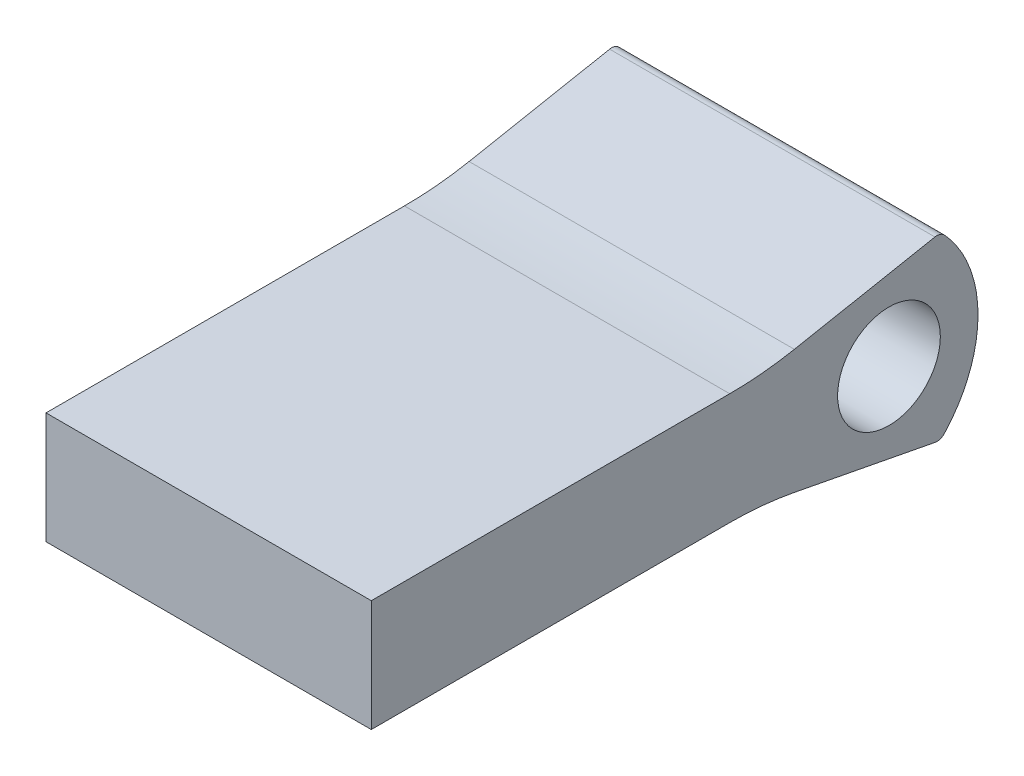
SolidWorks part; units mm, degrees
ref_plane "Front Plane" through (0, 0, 0) normal (0, 0, 1) x (1, 0, 0)
ref_plane "Top Plane" through (0, 0, 0) normal (0, 1, 0) x (1, 0, 0)
ref_plane "Right Plane" through (0, 0, 0) normal (1, 0, 0) x (0, 0, -1)
sketch "Sketch1" plane through (0, 0, 0) normal (0, 0, 1) x (1, 0, 0)
  line L1 (4.75, -1.63) -> (-4.75, -1.63)
  line L2 (4.75, -1.63) -> (4.75, 1.63)
  line L3 (4.75, 1.63) -> (-4.75, 1.63)
  line L4 (-4.75, -1.63) -> (-4.75, 1.63)
  line L5 (4.75, -1.63) -> (-4.75, 1.63) construction
  line L6 (4.75, 1.63) -> (-4.75, -1.63) construction
  point P0 (0, 0)
  dimension "D1" = 9.5
  dimension "D2" = 3.26
extrude "Boss-Extrude1" add sketch "Sketch1" along normal blind 11.42
sketch "Sketch3" plane through (0, 0, 0) normal (1, 0, 0) x (0, 0, -1)
  line L0 (0, 0) -> (5.2, 0) construction
  line L1 (0, -1.63) -> (0, 1.63) construction
  line L2 (5.2, 2.6292) -> (5.2, -2.6292) construction
  line L3 (0, 1.63) -> (5.2, 2.6292)
  line L4 (0, -1.63) -> (5.2, -2.6292)
  line L5 (0, -1.63) -> (0, 1.63)
  spline S0 degree 3 poles (5.2, -2.6292) (5.2831, -2.5471) (5.3638, -2.4595) (5.6098, -2.1644) (5.763, -1.9362) (6.0194, -1.4361) (6.1224, -1.1641) (6.2618, -0.5947) (6.2982, -0.2974) (6.2982, 0.2974) (6.2618, 0.5947) (6.1224, 1.1641) (6.0194, 1.4361) (5.763, 1.9362) (5.6098, 2.1644) (5.3638, 2.4595) (5.2831, 2.5471) (5.2, 2.6292) knots 0.163498 0.163498 0.163498 0.163498 0.204239 0.204239 0.292589 0.292589 0.380938 0.380938 0.469288 0.469288 0.557637 0.557637 0.645987 0.645987 0.734336 0.734336 0.775076 0.775076 0.775076 0.775076
  dimension "D1" = 5.2
  dimension "D2" = 5.2583
extrude "Boss-Extrude3" add sketch "Sketch3" against normal up to surface and the other way up to surface contours L4 S0 L3 L5 up to face at (-4.75, 0, 5.71) other way up to face at (4.75, 0, 5.71)
fillet "Fillet1" radius 0.3 2 edges at (0, 2.6292, -5.2) (0, -2.6292, -5.2)
sketch "Sketch4" plane through (4.75, 0, 0) normal (1, 0, 0) x (0, 0, -1)
  line L0 (3.6982, 0) -> (5.1982, 0) construction
  line L1 (0, 0) -> (6.2982, 0) construction
  circle A0 centre (3.6982, 0) radius 1.5
  spline S0 degree 3 poles (2991.5394, -266.3523) (-92.0902, -98.3449) (-6.4003, 16.5761) (5.6098, 2.1644) (5.763, 1.9362) (6.0194, 1.4361) (6.1224, 1.1641) (6.2618, 0.5947) (6.2982, 0.2974) (6.2982, -0.2974) (6.2618, -0.5947) (6.1224, -1.1641) (6.0194, -1.4361) (5.763, -1.9362) (5.6098, -2.1644) (-6.4001, -16.576) (-92.0887, 98.3427) (2991.4542, 266.3508) knots -6.011179 -6.011179 -6.011179 -6.011179 0.204239 0.204239 0.292588 0.292588 0.380938 0.380938 0.469287 0.469287 0.557637 0.557637 0.645986 0.645986 0.734336 0.734336 6.949696 6.949696 6.949696 6.949696 only from (5.3177, 2.5075) to (5.3177, -2.5075) construction
  spline S1 degree 3 poles (5.3177, 2.5075) (5.3597, 2.4619) (5.401, 2.4149) (5.6098, 2.1644) (5.763, 1.9362) (6.0194, 1.4361) (6.1224, 1.1641) (6.2618, 0.5947) (6.2982, 0.2974) (6.2982, -0.2974) (6.2618, -0.5947) (6.1224, -1.1641) (6.0194, -1.4361) (5.763, -1.9362) (5.6098, -2.1644) (5.401, -2.4149) (5.3597, -2.4619) (5.3177, -2.5075) knots 0.183007 0.183007 0.183007 0.183007 0.204239 0.204239 0.292588 0.292588 0.380938 0.380938 0.469287 0.469287 0.557637 0.557637 0.645986 0.645986 0.734336 0.734336 0.755568 0.755568 0.755568 0.755568 construction
  point P5 (0, 0)
  point P9 (0, 0)
  point P10 (3.6982, 0.4107)
  dimension "D1" = 1.1
  dimension "D2" = 3
extrude "Cut-Extrude1" cut sketch "Sketch4" against normal through all
fillet "Fillet2" radius 10 2 edges at (0, 1.63, 0) (0, -1.63, 0)
